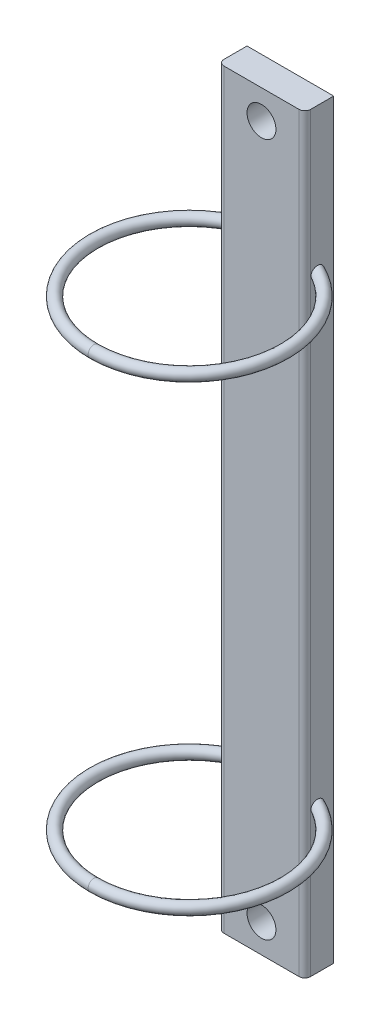
SolidWorks part; units mm, degrees
ref_plane "Front" through (0, 0, 0) normal (0, 0, 1) x (1, 0, 0)
ref_plane "Top" through (0, 0, 0) normal (0, 1, 0) x (1, 0, 0)
ref_plane "Right" through (0, 0, 0) normal (1, 0, 0) x (0, 0, -1)
sketch "Эскиз1" plane through (0, 0, 0) normal (0, 0, 1) x (1, 0, 0)
  line L0 (0, 0) -> (0, 60) construction
  line L5 (-7.5, -65) -> (7.5, -65)
  line L6 (-7.5, -65) -> (-7.5, 65)
  line L7 (-7.5, 65) -> (7.5, 65)
  line L8 (7.5, -65) -> (7.5, 65)
  line L9 (-7.5, -65) -> (7.5, 65) construction
  line L10 (-7.5, 65) -> (7.5, -65) construction
  line L11 (0, 0) -> (7.5, 0) construction
  circle A0 centre (0, 60) radius 2.5
  circle A1 centre (0, -60) radius 2.5
  point P0 (0, 0)
  dimension "D3" = 5
  dimension "D4" = 120
  dimension "D1" = 130
  dimension "D2" = 15
extrude "Бобышка-Вытянуть1" add sketch "Эскиз1" along normal blind 5
ref_plane "Плоскость1" through (0, 40, 0) normal (0, 1, 0) x (1, 0, 0)
sketch "Эскиз28" plane through (0, 40, 0) normal (0, 1, 0) x (1, 0, 0)
  line L0 (-7.5, 0) -> (7.5, 0) construction
  circle A0 centre (0, -17.5) radius 16.5
  dimension "D1" = 33
  dimension "D2" = 1
sweep "По траектории2" add path "Эскиз28" circular profile diameter 2 parameters "D3"=2
fillet "Скругление1" radius 1 2 edges at (-7.5, 0, 5) (7.5, 0, 5)
mirror "Зеркальное отражение1" about plane through (0, 0, 0) normal (0, 1, 0) of "По траектории2"
